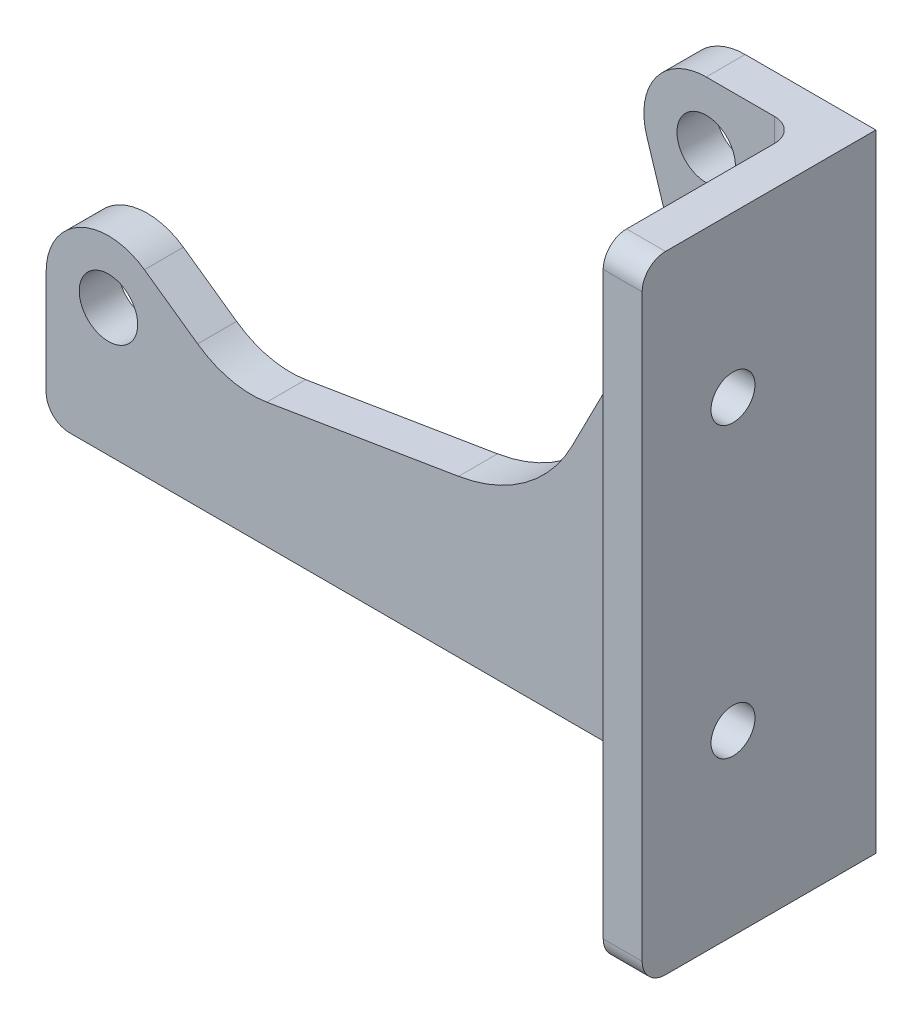
SolidWorks part; units mm, degrees
ref_plane "Front Plane" through (0, 0, 0) normal (0, 0, 1) x (1, 0, 0)
ref_plane "Top Plane" through (0, 0, 0) normal (0, 1, 0) x (1, 0, 0)
ref_plane "Right Plane" through (0, 0, 0) normal (1, 0, 0) x (0, 0, -1)
sketch "Sketch1" plane through (0, 0, 0) normal (0, 0, 1) x (1, 0, 0)
  line L1 (0, 0) -> (237.6666, 0)
  line L2 (0, 0) -> (0, 144.8708)
  line L3 (0, 144.8708) -> (237.6666, 144.8708)
  line L4 (237.6666, 0) -> (237.6666, 144.8708)
extrude "Boss-Extrude1" add sketch "Sketch1" along normal blind 6.35
sketch "Sketch5" plane through (0, 0, 0) normal (0, 0, -1) x (-1, 0, 0)
  line L0 (-189.7215, 90.7661) -> (-128.1772, 45.8357) construction
  line L1 (-167.6351, 56.4034) -> (-134.8707, 101.283) construction
  line L2 (-176.4898, 84.1608) -> (-185.8156, 65.4791)
  line L3 (-138.1333, 56.3519) -> (-153.665, 41.6474)
  line L6 (-189.7215, 105.5548) -> (-237.6666, 105.5548)
  line L7 (-237.6666, 0) -> (-237.6666, 144.8708) construction
  line L9 (-237.6666, 16.6072) -> (-121.3156, 16.6072)
  line L10 (-113.6956, 24.2272) -> (-113.6956, 45.8357)
  line L11 (-237.6666, 16.6072) -> (-263.6446, -9.3708)
  line L12 (-263.6446, -9.3708) -> (31.5253, -21.3837)
  line L13 (31.5253, -21.3837) -> (24.2737, 162.9725)
  line L14 (24.2737, 162.9725) -> (-280.2926, 162.9725)
  line L15 (-280.2926, 162.9725) -> (-237.6666, 105.5548)
  arc A0 (-113.6956, 24.2272) -> (-121.3156, 16.6072) centre (-121.3156, 24.2272) cw
  circle A3 centre (-128.1772, 45.8357) radius 4.7625 construction
  arc A4 (-176.4898, 84.1608) -> (-189.7215, 105.5548) centre (-189.7215, 90.7661) ccw
  arc A5 (-185.8156, 65.4791) -> (-153.665, 41.6474) centre (-167.6351, 56.4034) ccw
  arc A6 (-113.6956, 45.8357) -> (-138.1333, 56.3519) centre (-128.1772, 45.8357) ccw
  circle A7 centre (-128.1772, 45.8357) radius 4.7625
  circle A8 centre (-189.7215, 90.7661) radius 4.7625
  dimension "D1" = 20.32
  dimension "D2" = 7.62
sketch "Sketch6" plane through (0, 0, 0) normal (0, 0, -1) x (-1, 0, 0)
  line L0 (-118095.2215, -161477.136) -> (117792.7157, 161634.8225) construction
  line L1 (-237.6666, 102.1322) -> (-216.3581, 102.1333)
  line L4 (-216.3576, 91.9733) -> (-167.6351, 56.4034) construction
  line L5 (-189.7215, 90.7661) -> (-128.1772, 45.8357) construction
  line L6 (-212.944, -5.6593) -> (-135.3873, 100.5754) construction
  line L9 (0, 0) -> (-237.6666, 0) construction
  line L10 (-108.7525, 0) -> (33.7886, -29.4147)
  line L11 (33.7886, -29.4147) -> (48.6457, 190.5271)
  line L12 (48.6457, 190.5271) -> (-347.1116, 192.6613)
  line L13 (-347.1116, 192.6613) -> (-237.6666, 102.1322)
  line L14 (-108.7525, 20.8335) -> (-108.7525, 0)
  line L15 (-237.6666, 0) -> (-237.6666, 144.8708) construction
  line L16 (-206.6682, 88.917) -> (-209.8637, 78.7867)
  line L17 (-208.8959, 67.2586) -> (-194.4614, 39.0563)
  line L18 (-144.7256, 20.4111) -> (-175.9848, 25.5674)
  line L19 (-124.7755, 29.1312) -> (-133.4507, 23.0014)
  circle A0 centre (-216.3576, 91.9733) radius 4.7625
  arc A4 (-206.6682, 88.917) -> (-124.7755, 29.1312) centre (-155.6477, 72.8233) ccw construction
  circle A6 centre (-118.9125, 20.8335) radius 4.7625
  arc A7 (-108.7525, 20.8335) -> (-124.7755, 29.1312) centre (-118.9125, 20.8335) ccw
  arc A8 (-216.3581, 102.1333) -> (-206.6682, 88.917) centre (-216.3576, 91.9733) cw
  arc A9 (-208.8959, 67.2586) -> (-209.8637, 78.7867) centre (-195.3296, 74.2021) cw
  arc A10 (-133.4507, 23.0014) -> (-144.7256, 20.4111) centre (-142.2452, 35.4479) cw
  arc A11 (-175.9848, 25.5674) -> (-194.4614, 39.0563) centre (-171.8508, 50.6288) cw
  point P13 (-211.7444, 72.8242)
  point P29 (-138.5568, 19.3935)
  point P37 (-188.6247, 27.6524)
  dimension "D1" = 9.525
  dimension "D3" = 10.16
  dimension "D4" = 15.24
  dimension "D5" = 15.24
  dimension "D6" = 25.4
  dimension "D2" = 60.325
extrude "Cut-Extrude1" cut sketch "Sketch6" against normal through all
sketch "Sketch7" plane through (0, 0, 6.35) normal (0, 0, 1) x (1, 0, 0)
  line L1 (231.3166, 102.1325) -> (237.6666, 102.1322)
  line L2 (231.3166, 102.1325) -> (231.3166, 0)
  line L3 (231.3166, 0) -> (237.6666, 0)
  line L4 (237.6666, 102.1322) -> (237.6666, 0)
  line L5 (237.6666, 102.1322) -> (216.3581, 102.1333) construction
  dimension "D1" = 6.35
extrude "Boss-Extrude2" add sketch "Sketch7" along normal blind 31.75
sketch "Sketch8" plane through (231.3166, 0, 0) normal (-1, 0, 0) x (0, 0, 1)
  circle A0 centre (23.2891, 76.0306) radius 3.5814
  circle A1 centre (23.2891, 28.9823) radius 3.5814
  dimension "D1" = 7.1628
  dimension "D2" = 7.1628
extrude "Cut-Extrude2" cut sketch "Sketch8" against normal through all
fillet "Fillet1" radius 3.81 4 edges at (234.4916, 102.1324, 38.1) (234.4916, 0, 38.1) (108.7525, 0, 3.175) (231.3166, 51.0663, 6.35)
sketch "Sketch9" plane through (0, 0, 0) normal (0, 0, -1) x (-1, 0, 0)
  line L0 (-216.3576, 91.9733) -> (-118.9125, 20.8335)
  line L1 (-167.6351, 56.4034) -> (-186.8276, 30.114)
  arc A0 (-194.4614, 39.0563) -> (-175.9848, 25.5674) centre (-171.8508, 50.6288) ccw construction
ref_plane "Plane1" through (167.6351, 56.4034, 0) normal (-0.8077, -0.5896, 0) x (0, 0, 1)
ref_plane "Plane3" through (31.4211, -43.0396, 0) normal (0.5896, -0.8077, 0) x (-0.8077, -0.5896, 0)
